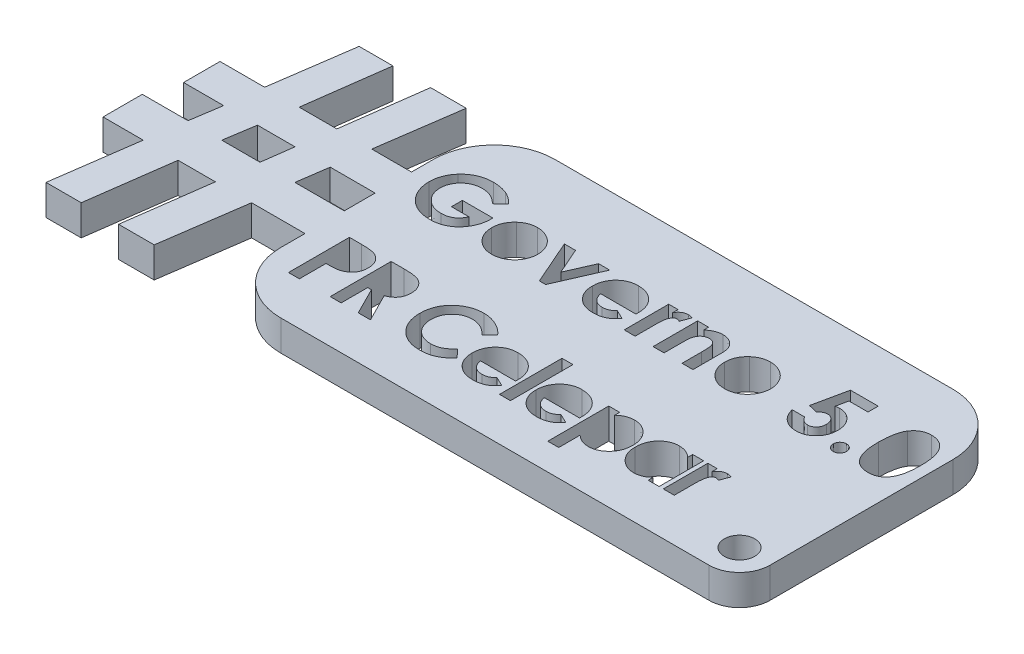
SolidWorks part; units mm, degrees
ref_plane "Front Plane" through (0, 0, 0) normal (0, 0, 1) x (1, 0, 0)
ref_plane "Top Plane" through (0, 0, 0) normal (0, 1, 0) x (1, 0, 0)
ref_plane "Right Plane" through (0, 0, 0) normal (1, 0, 0) x (0, 0, -1)
sketch "Sketch1" plane through (0, 0, 0) normal (0, 1, 0) x (1, 0, 0)
  line L1 (0, 0) -> (120, 0)
  line L2 (0, 0) -> (0, 45)
  line L3 (0, 45) -> (120, 45)
  line L4 (120, 0) -> (120, 45)
  dimension "D1" = 120
  dimension "D2" = 45
extrude "Boss-Extrude1" add sketch "Sketch1" along normal blind 5
sketch "Sketch2" plane through (0, 5, 0) normal (0, 1, 0) x (1, 0, 0)
  line L0 (6.244, 0) -> (0, 0)
  line L1 (0, 0) -> (120, 0) construction
  line L2 (0, 0) -> (0, 45)
  line L3 (0, 45) -> (12.6035, 45)
  line L4 (120, 45) -> (0, 45) construction
  line L5 (8.2186, 13.9722) -> (6.244, 0)
  line L6 (8.2186, 13.9722) -> (1.6284, 13.9722)
  line L7 (1.6284, 13.9722) -> (1.6284, 20.4105)
  line L8 (1.6284, 20.4105) -> (9.1284, 20.4105)
  line L9 (9.9032, 25.4739) -> (3.337, 25.4739)
  line L10 (3.337, 25.4739) -> (3.337, 31.447)
  line L11 (3.337, 31.447) -> (10.6556, 31.447)
  line L12 (12.0211, 0) -> (13.934, 13.9722)
  line L14 (20.0586, 13.9722) -> (18.1458, 0)
  line L15 (18.1458, 0) -> (12.0211, 0)
  line L16 (20.0586, 13.9722) -> (13.934, 13.9722)
  line L17 (9.9032, 25.4739) -> (9.1284, 20.4105)
  line L18 (15.4541, 25.4739) -> (21.6137, 25.4739)
  line L19 (21.6137, 25.4739) -> (20.9333, 20.4105)
  line L20 (20.9333, 20.4105) -> (14.6662, 20.4105)
  line L21 (14.6662, 20.4105) -> (15.4541, 25.4739)
  line L22 (18.1458, 45) -> (16.3245, 31.447)
  line L23 (16.3245, 31.447) -> (22.5024, 31.447)
  line L24 (22.5024, 31.447) -> (24.3237, 45)
  line L25 (24.3237, 45) -> (18.1458, 45)
  line L26 (12.6035, 45) -> (10.6556, 31.447)
  line L27 (30.1747, 45) -> (28.2268, 31.447)
  line L28 (28.2268, 31.447) -> (34.7513, 31.447)
  line L29 (34.7513, 31.447) -> (34.7513, 45)
  line L30 (34.7513, 45) -> (30.1747, 45)
  line L31 (34.7513, 25.4739) -> (27.389, 25.4739)
  line L32 (27.389, 25.4739) -> (26.6612, 20.4105)
  line L33 (26.6612, 20.4105) -> (34.7513, 20.4105)
  line L34 (34.7513, 20.4105) -> (34.7513, 25.4739)
  line L35 (25.9961, 13.9722) -> (23.9879, 0)
  line L36 (23.9879, 0) -> (34.7513, 0)
  line L37 (34.7513, 0) -> (34.7513, 13.9722)
  line L38 (34.7513, 13.9722) -> (25.9961, 13.9722)
  text T0 "<b><i>#</i></b>" font "Century Gothic" height 44
  line M4 (0, 45) -> (0, 0)
  line M5 (0, 0) -> (120, 0)
  line M7 (120, 45) -> (0, 45)
extrude "Cut-Extrude2" cut sketch "Sketch2" against normal blind 5 contours L33 L34 L31 L32 | L28 L29 L27 M7 | L37 L38 L35 M5 | L14 L16 L12 M5 | L23 L24 L22 M7 | L26 L5 L6 L7 L8 L17 L9 L10 L11 M7 M4 M5 | L21 L18 L19 L20
sketch "Sketch3" plane through (0, 5, 0) normal (0, 1, 0) x (1, 0, 0)
  text T0 "<b>Governo 5.0</b>" font "Century Gothic" height 10
extrude "Cut-Extrude3" cut sketch "Sketch3" against normal blind 5
sketch "Sketch4" plane through (0, 5, 0) normal (0, 1, 0) x (1, 0, 0)
  line L1 (67.5246, 32.7257) -> (71.7103, 32.7257)
  line L2 (67.5246, 32.7257) -> (67.5246, 30.6689)
  line L3 (67.5246, 30.6689) -> (71.7103, 30.6689)
  line L4 (71.7103, 32.7257) -> (71.7103, 30.6689)
  line L5 (113.0479, 34.9433) -> (117.0682, 34.9433)
  line L6 (113.0479, 34.9433) -> (113.0479, 27.7233)
  line L7 (113.0479, 27.7233) -> (117.0682, 27.7233)
  line L8 (117.0682, 34.9433) -> (117.0682, 27.7233)
  circle A0 centre (53.0641, 29.9496) radius 2.6051
  circle A1 centre (91.1925, 29.9496) radius 2.686
extrude "Cut-Extrude4" cut sketch "Sketch4" against normal blind 5
sketch "Sketch5" plane through (0, 5, 0) normal (0, 1, 0) x (1, 0, 0)
  text T0 "<b>PR Celepar</b>" font "Century Gothic" height 10
extrude "Cut-Extrude5" cut sketch "Sketch5" against normal blind 5
sketch "Sketch6" plane through (0, 5, 0) normal (0, 1, 0) x (1, 0, 0)
  line L1 (40.3342, 15.9486) -> (43.2779, 15.9486)
  line L2 (40.3342, 15.9486) -> (40.3342, 13.0006)
  line L3 (40.3342, 13.0006) -> (43.2779, 13.0006)
  line L4 (43.2779, 15.9486) -> (43.2779, 13.0006)
  line L5 (47.0924, 15.9486) -> (50.5535, 15.9486)
  line L6 (47.0924, 15.9486) -> (47.0924, 12.6564)
  line L7 (47.0924, 12.6564) -> (50.5535, 12.6564)
  line L8 (50.5535, 15.9486) -> (50.5535, 12.6564)
  line L9 (67.0122, 13.3354) -> (71.478, 13.3354)
  line L10 (67.0122, 13.3354) -> (67.0122, 10.9911)
  line L11 (67.0122, 10.9911) -> (71.478, 10.9911)
  line L12 (71.478, 13.3354) -> (71.478, 10.9911)
  line L13 (77.5205, 13.3354) -> (81.9942, 13.3354)
  line L14 (77.5205, 13.3354) -> (77.5205, 11.2492)
  line L15 (77.5205, 11.2492) -> (81.9942, 11.2492)
  line L16 (81.9942, 13.3354) -> (81.9942, 11.2492)
  circle A0 centre (87.913, 10.9911) radius 2.7607
  circle A1 centre (96.2652, 10.9911) radius 2.5927
extrude "Cut-Extrude6" cut sketch "Sketch6" against normal blind 5
fillet "Fillet1" radius 10 2 edges at (34.7513, 2.5, -45) (120, 2.5, -45)
fillet "Fillet2" radius 10 1 edges at (34.7513, 2.5, 0)
sketch "Sketch7" plane through (0, 5, 0) normal (0, 1, 0) x (1, 0, 0)
  line L0 (120, 0) -> (120, 35) construction
  line L1 (44.7513, 0) -> (120, 0) construction
  circle A0 centre (115, 5) radius 2.5
  dimension "D1" = 5
  dimension "D2" = 5
  dimension "D3" = 5
extrude "Cut-Extrude7" cut sketch "Sketch7" against normal blind 5
fillet "Fillet3" radius 5 1 edges at (120, 2.5, 0)
